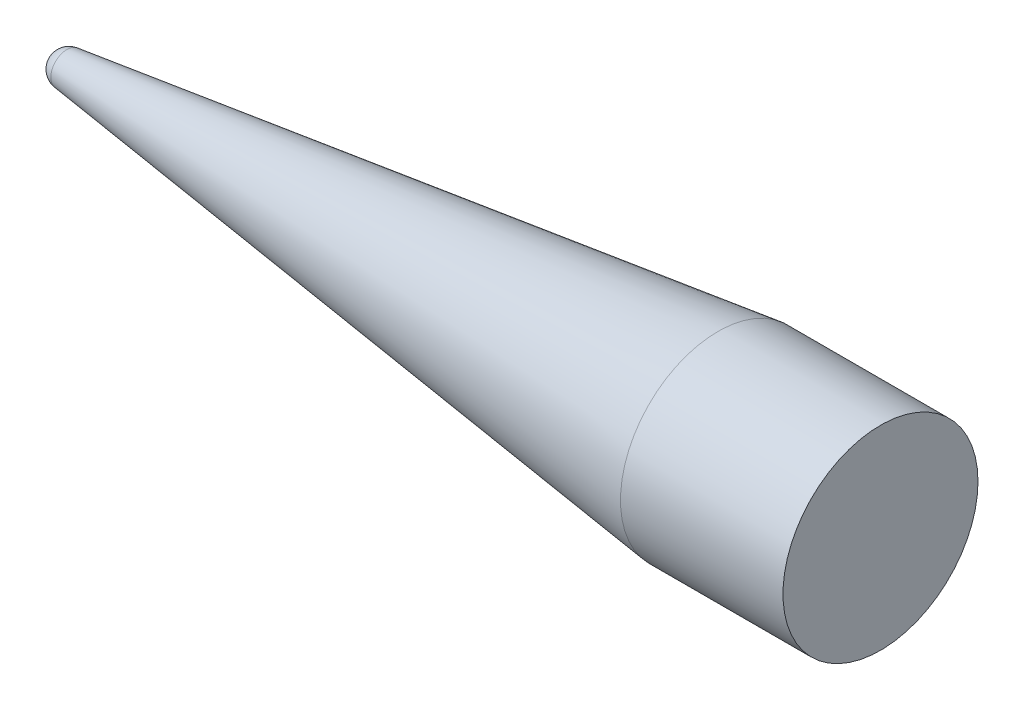
SolidWorks part; units mm, degrees
ref_plane "Front Plane" through (0, 0, 0) normal (0, 0, 1) x (1, 0, 0)
ref_plane "Top Plane" through (0, 0, 0) normal (0, 1, 0) x (1, 0, 0)
ref_plane "Right Plane" through (0, 0, 0) normal (1, 0, 0) x (0, 0, -1)
sketch "Sketch1" plane through (0, 0, 0) normal (0, 1, 0) x (1, 0, 0)
  line L0 (89.6907, 0) -> (609.6, 0)
  line L1 (609.6, 0) -> (609.6, 76.2)
  arc A0 (100.8154, 12.6019) -> (89.6907, 0) centre (102.3907, 0) ccw
  spline S0 degree 1 poles (0, 0) (609.6, 76.2) knots 0 0 1 1 construction
  spline S1 degree 1 poles (100.8154, 12.6019) (609.6, 76.2) knots 0.16538 0.16538 1 1
  point P3 (0, 0)
revolve "Revolve3" add sketch "Sketch1" angle 360 about L0
sketch "Sketch2" plane through (609.6, 0, 0) normal (1, 0, 0) x (0, 0, -1)
  circle A0 centre (0, 0) radius 76.2
extrude "Boss-Extrude1" add sketch "Sketch2" along normal blind 127
